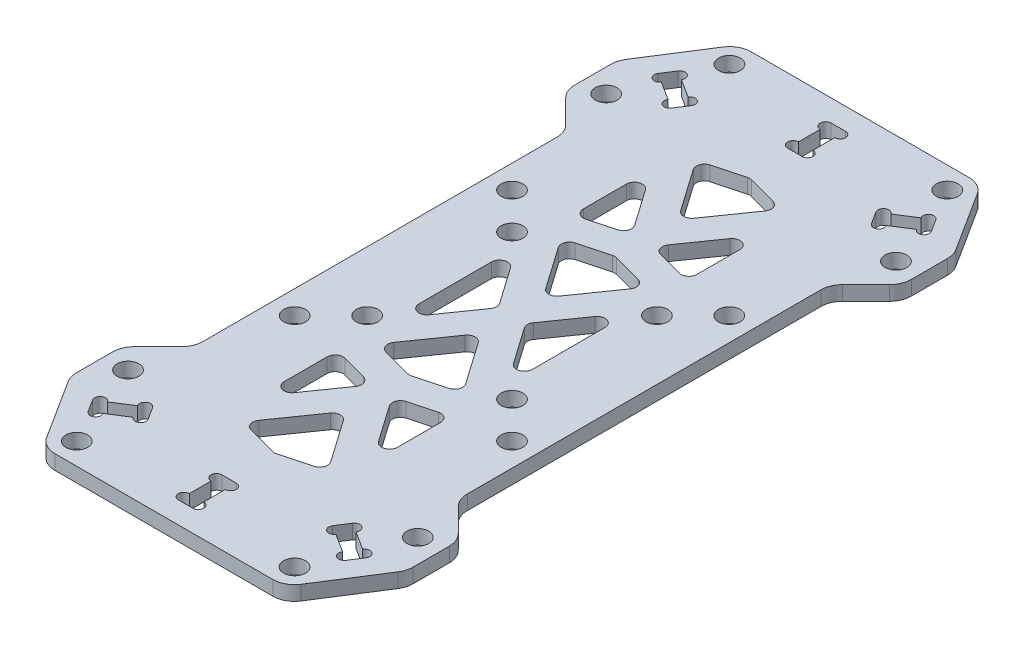
SolidWorks part; units mm, degrees
material "ABS"
ref_plane "Front Plane" through (0, 0, 0) normal (0, 0, 1) x (1, 0, 0)
ref_plane "Top Plane" through (0, 0, 0) normal (0, 1, 0) x (1, 0, 0)
ref_plane "Right Plane" through (0, 0, 0) normal (1, 0, 0) x (0, 0, -1)
sketch "Sketch11" plane through (0, 0, 0) normal (0, 1, 0) x (1, 0, 0)
  line L0 (0, 48.049) -> (0, 45.049)
  line L1 (0, 45.049) -> (1, 45.049)
  line L2 (1, 43.549) -> (1, 40.549)
  line L3 (0, 39.049) -> (1, 39.049)
  line L4 (0.9011, 5.5604) -> (4.9583, 11.3547)
  line L7 (18.23, 0) -> (18.23, 24.4052)
  line L8 (19.1087, 26.5265) -> (22.3513, 29.7692)
  line L9 (23.23, 31.8905) -> (23.23, 36.8905)
  line L10 (22.7602, 38.5024) -> (17.5626, 46.6609)
  line L11 (15.0325, 48.049) -> (0, 48.049)
  line L12 (13.9973, 38.2986) -> (16.5275, 39.9105)
  line L13 (17.7926, 40.7165) -> (18.8672, 39.0297)
  line L14 (17.6021, 38.2237) -> (15.0719, 36.6118)
  line L15 (12.7322, 37.4927) -> (13.8068, 35.8059)
  line L16 (-44.2539, 0) -> (44.2539, 0) construction
  line L17 (7.8346, 17.6869) -> (7.8346, 23.625)
  line L18 (4.3419, 13.0481) -> (0.2847, 14.1353)
  line L19 (2.3325, 0.6309) -> (5.8336, 5.6309)
  line L20 (7.8346, 5) -> (7.8346, 0)
  line L21 (2.1336, 0) -> (0, 0)
  line L22 (7.8346, 0) -> (18.23, 0)
  line L24 (0, 5.0913) -> (0, 0)
  line L25 (0, -44.7868) -> (0, 44.7868) construction
  line L26 (5.8336, 24.256) -> (2.3325, 19.256)
  line L27 (2.9489, 17.5625) -> (6.4499, 16.6244)
  line L28 (0.9011, 24.1854) -> (4.9614, 29.9842)
  line L29 (4.3451, 31.6776) -> (0.2847, 32.7656)
  line L30 (0, 32.8031) -> (0, 39.049)
  line L31 (0, 23.7163) -> (0, 14.1728)
  arc A0 (1, 45.049) -> (1, 43.549) centre (1, 44.299) cw
  arc A1 (1, 39.049) -> (1, 40.549) centre (1, 39.799) ccw
  arc A2 (15.0325, 48.049) -> (17.5626, 46.6609) centre (15.0325, 45.049) cw
  arc A3 (22.7602, 38.5024) -> (23.23, 36.8905) centre (20.23, 36.8905) cw
  arc A4 (23.23, 31.8905) -> (22.3513, 29.7692) centre (20.23, 31.8905) cw
  arc A5 (19.1087, 26.5265) -> (18.23, 24.4052) centre (21.23, 24.4052) ccw
  arc A6 (17.7926, 40.7165) -> (16.5275, 39.9105) centre (17.16, 40.3135) ccw
  arc A7 (18.8672, 39.0297) -> (17.6021, 38.2237) centre (18.2346, 38.6267) cw
  arc A8 (13.8068, 35.8059) -> (15.0719, 36.6118) centre (14.4394, 36.2089) ccw
  arc A9 (12.7322, 37.4927) -> (13.9973, 38.2986) centre (13.3648, 37.8956) cw
  circle A10 centre (15.0325, 45.049) radius 1.5
  arc A13 (4.3419, 13.0481) -> (4.9583, 11.3547) centre (4.0572, 11.9856) cw
  arc A16 (0.9011, 5.5604) -> (0, 5.0913) centre (0, 6.1913) cw
  arc A17 (0.2847, 14.1353) -> (0, 14.1728) centre (0, 13.0728) ccw
  arc A18 (5.8336, 5.6309) -> (7.8346, 5) centre (6.7346, 5) cw
  arc A19 (2.3325, 0.6309) -> (2.1336, 0) centre (3.2336, 0) ccw
  arc A20 (7.8346, 23.625) -> (5.8336, 24.256) centre (6.7346, 23.625) ccw
  arc A21 (7.8346, 17.6869) -> (6.4499, 16.6244) centre (6.7346, 17.6869) cw
  arc A22 (2.3325, 19.256) -> (2.9489, 17.5625) centre (3.2336, 18.625) ccw
  arc A23 (4.3451, 31.6776) -> (4.9614, 29.9842) centre (4.0604, 30.6151) cw
  arc A24 (0.9011, 24.1854) -> (0, 23.7163) centre (0, 24.8163) cw
  arc A25 (0.2847, 32.7656) -> (0, 32.8031) centre (0, 31.7031) ccw
  circle A26 centre (10, 10) radius 1.5
  circle A27 centre (20, 33) radius 1.5
  circle A28 centre (15, 15) radius 1.5
  point P80 (0, 0)
  point P82 (0, 0)
  dimension "D2" = 3
  dimension "D3" = 3
  dimension "D4" = 3
  dimension "D5" = 3
  dimension "D11" = 3
  dimension "D19" = 0.75
  dimension "D20" = 0.75
  dimension "D21" = 32.5
  dimension "D22" = 1.1
  dimension "D23" = 1.1
  dimension "D26" = 5
  dimension "D28" = 1.1
  dimension "D9" = 1.1
  dimension "D25" = 1.1
  dimension "D32" = 1.1
  dimension "D33" = 1.1
  dimension "D34" = 1.1
  dimension "D35" = 1.1
  dimension "D36" = 1.1
  dimension "D37" = 1.1
  dimension "D39" = 3
  dimension "D43" = 3
  dimension "D42" = 3
  dimension "D1" = 5
  dimension "D6" = 6
  dimension "D7" = 2
  dimension "D8" = 6
  dimension "D10" = 3
  dimension "D12" = 48.049
  dimension "D13" = 1
  dimension "D14" = 45
  dimension "D15" = 5
  dimension "D16" = 4.9954
  dimension "D17" = 9.4223
  dimension "D18" = 3
  dimension "D24" = 15
  dimension "D27" = 4
  dimension "D29" = 55
  dimension "D30" = 23.23
  dimension "D31" = 4
  dimension "D38" = 4
  dimension "D40" = 10
  dimension "D41" = 10
  dimension "D44" = 33
  dimension "D45" = 20
  dimension "D46" = 15
  dimension "D47" = 15
extrude "Boss-Extrude1" add sketch "Sketch11" along normal blind 2
mirror "Mirror10" about plane through (0, 0, 0) normal (1, 0, 0) of "Boss-Extrude1"
mirror "Mirror11" about plane through (0, 0, 0) normal (0, 0, 1) of "Mirror10", "Boss-Extrude1"
